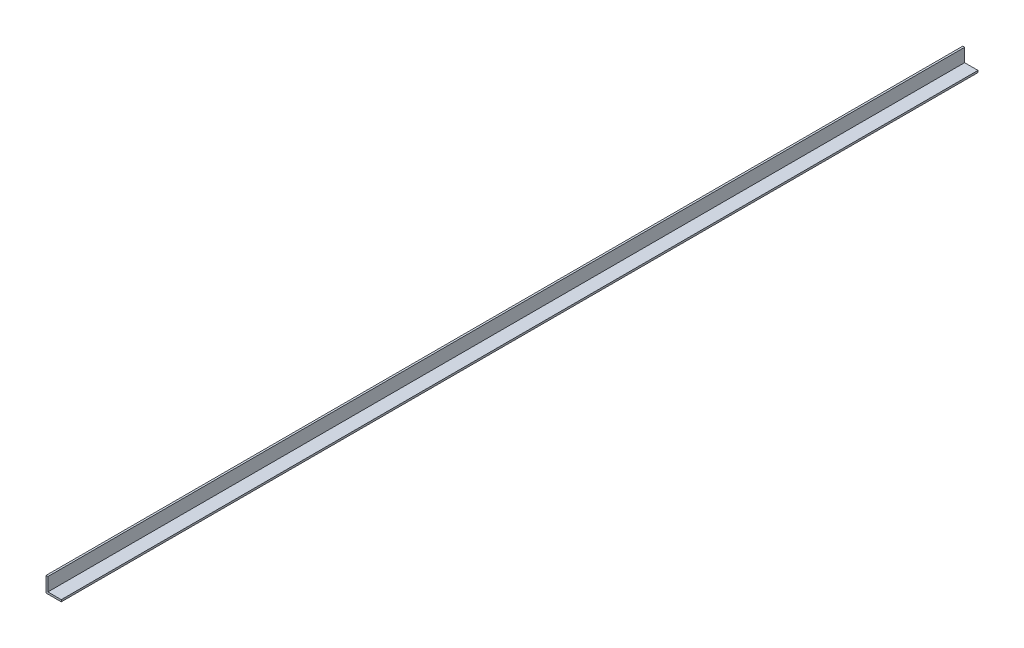
SolidWorks part; units mm, degrees
material "ASTM A36 Acero"
ref_plane "Alzado" through (0, 0, 0) normal (0, 0, 1) x (1, 0, 0)
ref_plane "Planta" through (0, 0, 0) normal (0, 1, 0) x (1, 0, 0)
ref_plane "Vista lateral" through (0, 0, 0) normal (1, 0, 0) x (0, 0, -1)
sketch "Croquis1" plane through (0, 0, 0) normal (0, 0, 1) x (1, 0, 0)
  line L0 (0, 101.6) -> (0, 0)
  line L1 (0, 0) -> (101.6, 0)
  line L2 (101.6, 0) -> (101.6, 12.7)
  line L3 (101.6, 12.7) -> (12.7, 12.7)
  line L4 (12.7, 12.7) -> (12.7, 101.6)
  line L5 (12.7, 101.6) -> (0, 101.6)
  dimension "D1" = 12.7
  dimension "D2" = 101.6
extrude "Saliente-Extruir1" add sketch "Croquis1" against normal blind 6100
